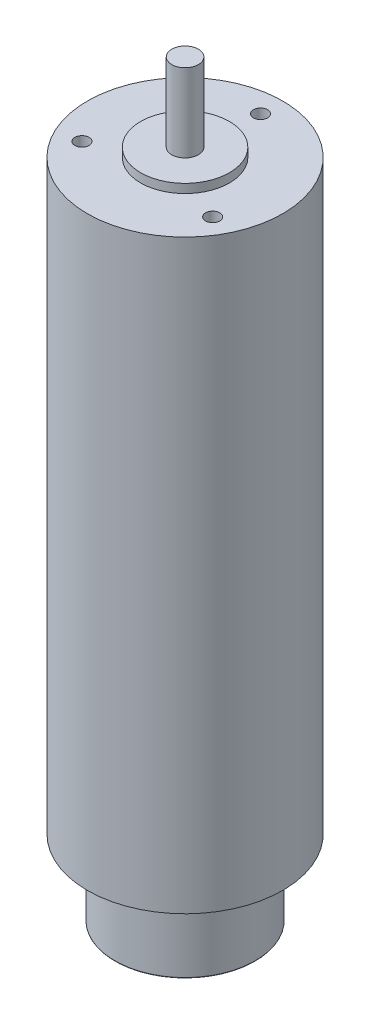
SolidWorks part; units mm, degrees
ref_plane "정면" through (0, 0, 0) normal (0, 0, 1) x (1, 0, 0)
ref_plane "윗면" through (0, 0, 0) normal (0, 1, 0) x (1, 0, 0)
ref_plane "우측면" through (0, 0, 0) normal (1, 0, 0) x (0, 0, -1)
sketch "스케치1" plane through (0, 0, 0) normal (0, 1, 0) x (1, 0, 0)
  circle A0 centre (0, 0) radius 11
  dimension "D1" = 22
extrude "보스-돌출1" add sketch "스케치1" along normal blind 66
sketch "스케치2" plane through (0, 66, 0) normal (0, 1, 0) x (1, 0, 0)
  circle A0 centre (0, 0) radius 5
  dimension "D1" = 10
extrude "보스-돌출2" add sketch "스케치2" along normal blind 1 separate body
sketch "스케치3" plane through (0, 67, 0) normal (0, 1, 0) x (1, 0, 0)
  circle A0 centre (0, 0) radius 1.5
  dimension "D1" = 3
extrude "보스-돌출3" add sketch "스케치3" along normal blind 8.8 separate body
sketch "스케치4" plane through (0, 0, 0) normal (0, -1, 0) x (1, 0, 0)
  circle A0 centre (0, 0) radius 7.9
  dimension "D1" = 15.8
extrude "보스-돌출4" add sketch "스케치4" along normal blind 8.5 separate body
fillet "필렛2" radius 0.1 1 edges at (0, -8.5, -7.9)
sketch "스케치5" plane through (0, 75.8, 0) normal (0, 1, 0) x (1, 0, 0)
  line L1 (-3.1841, 3.5344) -> (3.6784, 3.5344)
  line L2 (-3.1841, 3.5344) -> (-3.1841, 1)
  line L3 (-3.1841, 1) -> (3.6784, 1)
  line L4 (3.6784, 3.5344) -> (3.6784, 1)
  circle A0 centre (0, 0) radius 1.5 construction
  dimension "D1" = 1
hole_wizard "M2 나사 구멍1" positions "스케치6" profile "스케치8" tap size "M2" standard "ISO"
sketch "스케치6" plane through (0, 66, 0) normal (0, 1, 0) x (1, 0, 0)
  circle A0 centre (0, 0) radius 5 construction
  point P0 (0, 8.5)
  dimension "D1" = 8.5
sketch "스케치8" plane through (0, 66, -8.5) normal (1, 0, 0) x (0, 0, 1)
  line L0 (0, 0) -> (0, 5.4807)
  line L1 (0, 5.4807) -> (0.8, 5)
  line L2 (0.8, 5) -> (0.8, 0)
  line L5 (0.8, 0) -> (0, 0)
  line L10 (0, 5.4807) -> (-0.8, 5) construction
  line L11 (0, -6.35) -> (0, 107.95) construction
  dimension "탭 드릴 지름" = 1.6
  dimension "탭 드릴 깊이" = 5
  dimension "드릴 각도" = 118
cosmetic thread "구멍 나사산1" parameters "D1"=4, "D2"=2
pattern_circular "원형 패턴2" count 3 every 120 about axis through (0, 0, 0) along (0, 1, 0) of "M2 나사 구멍1"
